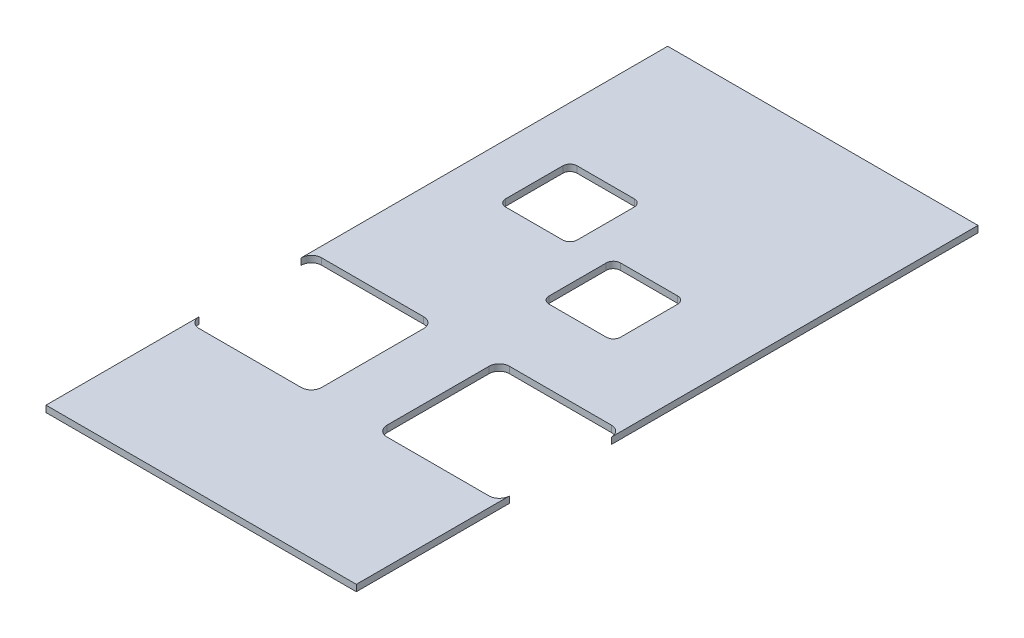
SolidWorks part; units mm, degrees
material "Oak"
ref_plane "Front Plane" through (0, 0, 0) normal (0, 0, 1) x (1, 0, 0)
ref_plane "Top Plane" through (0, 0, 0) normal (0, 1, 0) x (1, 0, 0)
ref_plane "Right Plane" through (0, 0, 0) normal (1, 0, 0) x (0, 0, -1)
sketch "Sketch1" plane through (0, 0, 0) normal (0, 1, 0) x (1, 0, 0)
  line L1 (-139.858, 348.6213) -> (164.142, 348.6213)
  line L2 (-139.858, 348.6213) -> (-139.858, -260.3787)
  line L3 (-139.858, -260.3787) -> (164.142, -260.3787)
  line L4 (164.142, 348.6213) -> (164.142, -260.3787)
  dimension "D1" = 304
  dimension "D2" = 609
extrude "Boss-Extrude1" add sketch "Sketch1" along normal blind 6.35 contours L2 L3 L4 L1
sketch "Sketch3" plane through (0, 6.35, 0) normal (0, 1, 0) x (1, 0, 0)
  line L0 (-139.858, -260.3787) -> (164.142, -260.3787) construction
  line L1 (154.142, -120.3787) -> (54.142, -120.3787)
  line L2 (164.142, -110.3787) -> (164.142, -10.3787)
  line L3 (154.142, -0.3787) -> (54.142, -0.3787)
  line L4 (44.142, -110.3787) -> (44.142, -10.3787)
  line L5 (-129.858, -120.3787) -> (-29.858, -120.3787)
  line L6 (-139.858, -110.3787) -> (-139.858, -10.3787)
  line L7 (-129.858, -0.3787) -> (-29.858, -0.3787)
  line L8 (-19.858, -110.3787) -> (-19.858, -10.3787)
  arc A0 (44.142, -110.3787) -> (54.142, -120.3787) centre (54.142, -110.3787) ccw
  arc A1 (154.142, -120.3787) -> (164.142, -110.3787) centre (154.142, -110.3787) ccw
  arc A2 (164.142, -10.3787) -> (154.142, -0.3787) centre (154.142, -10.3787) ccw
  arc A3 (54.142, -0.3787) -> (44.142, -10.3787) centre (54.142, -10.3787) ccw
  arc A4 (-29.858, -0.3787) -> (-19.858, -10.3787) centre (-29.858, -10.3787) cw
  arc A5 (-19.858, -110.3787) -> (-29.858, -120.3787) centre (-29.858, -110.3787) cw
  arc A6 (-129.858, -120.3787) -> (-139.858, -110.3787) centre (-129.858, -110.3787) cw
  arc A7 (-139.858, -10.3787) -> (-129.858, -0.3787) centre (-129.858, -10.3787) cw
  point P12 (44.142, -120.3787)
  point P15 (164.142, -120.3787)
  point P18 (164.142, -0.3787)
  point P23 (-19.858, -0.3787)
  point P28 (-139.858, -120.3787)
  point P31 (-139.858, -0.3787)
  dimension "D7" = 10
  dimension "D1" = 120
  dimension "D2" = 120
  dimension "D3" = 140
  dimension "D4" = 140
  dimension "D5" = 120
  dimension "D6" = 120
extrude "Cut-Extrude1" cut sketch "Sketch3" against normal through all
sketch "Sketch4" plane through (0, 6.35, 0) normal (0, 1, 0) x (1, 0, 0)
  line L1 (20.9069, 141.6824) -> (76.9069, 141.6824)
  line L2 (13.9069, 134.6824) -> (13.9069, 78.6824)
  line L3 (20.9069, 71.6824) -> (76.9069, 71.6824)
  line L4 (83.9069, 134.6824) -> (83.9069, 78.6824)
  line L9 (-82.7769, 202.8094) -> (-26.7769, 202.8094)
  line L10 (-89.7769, 195.8094) -> (-89.7769, 139.8094)
  line L11 (-82.7769, 132.8094) -> (-26.7769, 132.8094)
  line L12 (-19.7769, 195.8094) -> (-19.7769, 139.8094)
  arc A0 (83.9069, 78.6824) -> (76.9069, 71.6824) centre (76.9069, 78.6824) cw
  arc A1 (20.9069, 71.6824) -> (13.9069, 78.6824) centre (20.9069, 78.6824) cw
  arc A2 (83.9069, 134.6824) -> (76.9069, 141.6824) centre (76.9069, 134.6824) ccw
  arc A3 (20.9069, 141.6824) -> (13.9069, 134.6824) centre (20.9069, 134.6824) ccw
  arc A4 (-26.7769, 202.8094) -> (-19.7769, 195.8094) centre (-26.7769, 195.8094) cw
  arc A5 (-26.7769, 132.8094) -> (-19.7769, 139.8094) centre (-26.7769, 139.8094) ccw
  arc A6 (-89.7769, 139.8094) -> (-82.7769, 132.8094) centre (-82.7769, 139.8094) ccw
  arc A7 (-89.7769, 195.8094) -> (-82.7769, 202.8094) centre (-82.7769, 195.8094) cw
  point P6 (83.9069, 71.6824)
  point P15 (83.9069, 141.6824)
  point P18 (13.9069, 141.6824)
  point P21 (-19.7769, 202.8094)
  point P26 (-89.7769, 132.8094)
  point P29 (-89.7769, 202.8094)
  dimension "D5" = 7
  dimension "D1" = 70
  dimension "D2" = 70
  dimension "D3" = 70
  dimension "D4" = 70
extrude "Cut-Extrude3" cut sketch "Sketch4" against normal through all
